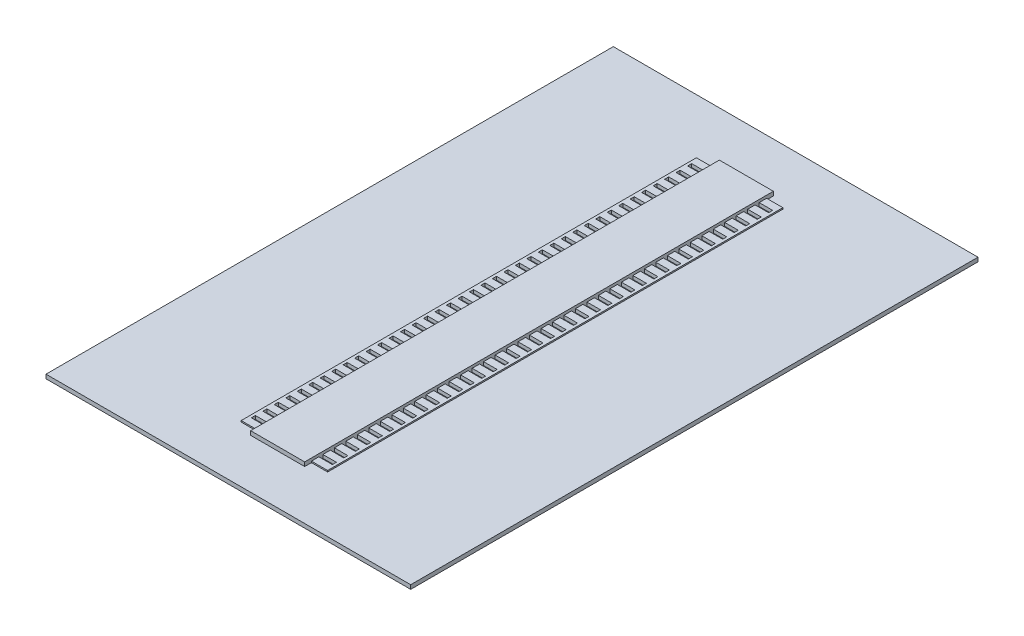
SolidWorks part; units mm, degrees
ref_plane "Front Plane" through (0, 0, 0) normal (0, 0, 1) x (1, 0, 0)
ref_plane "Top Plane" through (0, 0, 0) normal (0, 1, 0) x (1, 0, 0)
ref_plane "Right Plane" through (0, 0, 0) normal (1, 0, 0) x (0, 0, -1)
sketch "Sketch1" plane through (0, 0, 0) normal (0, 1, 0) x (1, 0, 0)
  line L1 (-13.5, 21) -> (13.5, 21)
  line L2 (-13.5, 21) -> (-13.5, -21)
  line L3 (-13.5, -21) -> (13.5, -21)
  line L4 (13.5, 21) -> (13.5, -21)
  line L5 (-13.5, 21) -> (13.5, -21) construction
  line L6 (-13.5, -21) -> (13.5, 21) construction
  point P0 (0, 0)
extrude "Boss-Extrude1" add sketch "Sketch1" along normal blind 0.3
sketch "Sketch2" plane through (0, 0.3, 0) normal (0, 1, 0) x (1, 0, 0)
  line L1 (-2, 17.35) -> (2, 17.35)
  line L2 (-2, 17.35) -> (-2, -17.35)
  line L3 (-2, -17.35) -> (2, -17.35)
  line L4 (2, 17.35) -> (2, -17.35)
  line L5 (-2, 17.35) -> (2, -17.35) construction
  line L6 (-2, -17.35) -> (2, 17.35) construction
  point P0 (0, 0)
extrude "Boss-Extrude2" add sketch "Sketch2" along normal blind 0.3
sketch "Sketch3" plane through (0, 0.3, 0) normal (0, 1, 0) x (1, 0, 0)
  line L0 (2, -17.35) -> (2, 17.35) construction
  line L1 (2, 16.85) -> (3.2, 16.85)
  line L2 (2, 16.85) -> (2, -16.85)
  line L3 (3.2, 16.85) -> (3.2, -16.85)
  line L4 (2, -16.85) -> (3.2, -16.85)
  line L5 (2, -17.35) -> (2, 17.35) construction
  line L6 (-12.7201, 0) -> (12.7201, 0) construction
  line L7 (0, 20.1281) -> (0, -20.1281) construction
  line L8 (-3.2, 16.85) -> (-3.2, -16.85)
  line L9 (-2, -16.85) -> (-3.2, -16.85)
  line L10 (-2, 16.85) -> (-2, -16.85)
  line L11 (-2, 16.85) -> (-3.2, 16.85)
  point P0 (2, 0)
  point P9 (3.2, 0)
  point P13 (0, 0)
  point P17 (0, 0)
extrude "Boss-Extrude4" add sketch "Sketch3" along normal blind 0.1
sketch "Sketch8" plane through (0, 0.4, 0) normal (0, 1, 0) x (1, 0, 0)
  line L0 (2, 16.3) -> (3, 16.3)
  line L1 (2, 16.3) -> (2, 16)
  line L2 (3, 16.3) -> (3, 16)
  line L3 (2, 16) -> (3, 16)
  line L4 (2, 16.85) -> (2, -16.85) construction
  line L5 (-3, 16.3) -> (-2, 16.3)
  line L6 (-3, 16.3) -> (-3, 16)
  line L7 (-3, 16) -> (-2, 16)
  line L8 (-2, 16.3) -> (-2, 16)
  line L9 (-3, 15.45) -> (-2, 15.45)
  line L10 (-3, 15.45) -> (-3, 15.15)
  line L11 (-3, 15.15) -> (-2, 15.15)
  line L12 (-2, 15.45) -> (-2, 15.15)
  line L13 (-3, 14.6) -> (-2, 14.6)
  line L14 (-3, 14.6) -> (-3, 14.3)
  line L15 (-3, 14.3) -> (-2, 14.3)
  line L16 (-2, 14.6) -> (-2, 14.3)
  line L17 (-3, 13.75) -> (-2, 13.75)
  line L18 (-3, 13.75) -> (-3, 13.45)
  line L19 (-3, 13.45) -> (-2, 13.45)
  line L20 (-2, 13.75) -> (-2, 13.45)
  line L21 (-3, 12.9) -> (-2, 12.9)
  line L22 (-3, 12.9) -> (-3, 12.6)
  line L23 (-3, 12.6) -> (-2, 12.6)
  line L24 (-2, 12.9) -> (-2, 12.6)
  line L25 (-3, 12.05) -> (-2, 12.05)
  line L26 (-3, 12.05) -> (-3, 11.75)
  line L27 (-3, 11.75) -> (-2, 11.75)
  line L28 (-2, 12.05) -> (-2, 11.75)
  line L29 (-3, 11.2) -> (-2, 11.2)
  line L30 (-3, 11.2) -> (-3, 10.9)
  line L31 (-3, 10.9) -> (-2, 10.9)
  line L32 (-2, 11.2) -> (-2, 10.9)
  line L33 (-3, 10.35) -> (-2, 10.35)
  line L34 (-3, 10.35) -> (-3, 10.05)
  line L35 (-3, 10.05) -> (-2, 10.05)
  line L36 (-2, 10.35) -> (-2, 10.05)
  line L37 (-3, 9.5) -> (-2, 9.5)
  line L38 (-3, 9.5) -> (-3, 9.2)
  line L39 (-3, 9.2) -> (-2, 9.2)
  line L40 (-2, 9.5) -> (-2, 9.2)
  line L41 (-3, 8.65) -> (-2, 8.65)
  line L42 (-3, 8.65) -> (-3, 8.35)
  line L43 (-3, 8.35) -> (-2, 8.35)
  line L44 (-2, 8.65) -> (-2, 8.35)
  line L45 (-3, 7.8) -> (-2, 7.8)
  line L46 (-3, 7.8) -> (-3, 7.5)
  line L47 (-3, 7.5) -> (-2, 7.5)
  line L48 (-2, 7.8) -> (-2, 7.5)
  line L49 (-3, 6.95) -> (-2, 6.95)
  line L50 (-3, 6.95) -> (-3, 6.65)
  line L51 (-3, 6.65) -> (-2, 6.65)
  line L52 (-2, 6.95) -> (-2, 6.65)
  line L53 (-3, 6.1) -> (-2, 6.1)
  line L54 (-3, 6.1) -> (-3, 5.8)
  line L55 (-3, 5.8) -> (-2, 5.8)
  line L56 (-2, 6.1) -> (-2, 5.8)
  line L57 (-3, 5.25) -> (-2, 5.25)
  line L58 (-3, 5.25) -> (-3, 4.95)
  line L59 (-3, 4.95) -> (-2, 4.95)
  line L60 (-2, 5.25) -> (-2, 4.95)
  line L61 (-3, 4.4) -> (-2, 4.4)
  line L62 (-3, 4.4) -> (-3, 4.1)
  line L63 (-3, 4.1) -> (-2, 4.1)
  line L64 (-2, 4.4) -> (-2, 4.1)
  line L65 (-3, 3.55) -> (-2, 3.55)
  line L66 (-3, 3.55) -> (-3, 3.25)
  line L67 (-3, 3.25) -> (-2, 3.25)
  line L68 (-2, 3.55) -> (-2, 3.25)
  line L69 (-3, 2.7) -> (-2, 2.7)
  line L70 (-3, 2.7) -> (-3, 2.4)
  line L71 (-3, 2.4) -> (-2, 2.4)
  line L72 (-2, 2.7) -> (-2, 2.4)
  line L73 (-3, 1.85) -> (-2, 1.85)
  line L74 (-3, 1.85) -> (-3, 1.55)
  line L75 (-3, 1.55) -> (-2, 1.55)
  line L76 (-2, 1.85) -> (-2, 1.55)
  line L77 (-3, 1) -> (-2, 1)
  line L78 (-3, 1) -> (-3, 0.7)
  line L79 (-3, 0.7) -> (-2, 0.7)
  line L80 (-2, 1) -> (-2, 0.7)
  line L81 (-3, 0.15) -> (-2, 0.15)
  line L82 (-3, 0.15) -> (-3, -0.15)
  line L83 (-3, -0.15) -> (-2, -0.15)
  line L84 (-2, 0.15) -> (-2, -0.15)
  line L85 (-3, -0.7) -> (-2, -0.7)
  line L86 (-3, -0.7) -> (-3, -1)
  line L87 (-3, -1) -> (-2, -1)
  line L88 (-2, -0.7) -> (-2, -1)
  line L89 (-3, -1.55) -> (-2, -1.55)
  line L90 (-3, -1.55) -> (-3, -1.85)
  line L91 (-3, -1.85) -> (-2, -1.85)
  line L92 (-2, -1.55) -> (-2, -1.85)
  line L93 (-3, -2.4) -> (-2, -2.4)
  line L94 (-3, -2.4) -> (-3, -2.7)
  line L95 (-3, -2.7) -> (-2, -2.7)
  line L96 (-2, -2.4) -> (-2, -2.7)
  line L97 (-3, -3.25) -> (-2, -3.25)
  line L98 (-3, -3.25) -> (-3, -3.55)
  line L99 (-3, -3.55) -> (-2, -3.55)
  line L100 (-2, -3.25) -> (-2, -3.55)
  line L101 (-3, -4.1) -> (-2, -4.1)
  line L102 (-3, -4.1) -> (-3, -4.4)
  line L103 (-3, -4.4) -> (-2, -4.4)
  line L104 (-2, -4.1) -> (-2, -4.4)
  line L105 (-3, -4.95) -> (-2, -4.95)
  line L106 (-3, -4.95) -> (-3, -5.25)
  line L107 (-3, -5.25) -> (-2, -5.25)
  line L108 (-2, -4.95) -> (-2, -5.25)
  line L109 (-3, -5.8) -> (-2, -5.8)
  line L110 (-3, -5.8) -> (-3, -6.1)
  line L111 (-3, -6.1) -> (-2, -6.1)
  line L112 (-2, -5.8) -> (-2, -6.1)
  line L113 (-3, -6.65) -> (-2, -6.65)
  line L114 (-3, -6.65) -> (-3, -6.95)
  line L115 (-3, -6.95) -> (-2, -6.95)
  line L116 (-2, -6.65) -> (-2, -6.95)
  line L117 (-3, -7.5) -> (-2, -7.5)
  line L118 (-3, -7.5) -> (-3, -7.8)
  line L119 (-3, -7.8) -> (-2, -7.8)
  line L120 (-2, -7.5) -> (-2, -7.8)
  line L121 (-3, -8.35) -> (-2, -8.35)
  line L122 (-3, -8.35) -> (-3, -8.65)
  line L123 (-3, -8.65) -> (-2, -8.65)
  line L124 (-2, -8.35) -> (-2, -8.65)
  line L125 (-3, -9.2) -> (-2, -9.2)
  line L126 (-3, -9.2) -> (-3, -9.5)
  line L127 (-3, -9.5) -> (-2, -9.5)
  line L128 (-2, -9.2) -> (-2, -9.5)
  line L129 (-3, -10.05) -> (-2, -10.05)
  line L130 (-3, -10.05) -> (-3, -10.35)
  line L131 (-3, -10.35) -> (-2, -10.35)
  line L132 (-2, -10.05) -> (-2, -10.35)
  line L133 (-3, -10.9) -> (-2, -10.9)
  line L134 (-3, -10.9) -> (-3, -11.2)
  line L135 (-3, -11.2) -> (-2, -11.2)
  line L136 (-2, -10.9) -> (-2, -11.2)
  line L137 (-3, -11.75) -> (-2, -11.75)
  line L138 (-3, -11.75) -> (-3, -12.05)
  line L139 (-3, -12.05) -> (-2, -12.05)
  line L140 (-2, -11.75) -> (-2, -12.05)
  line L141 (-3, -12.6) -> (-2, -12.6)
  line L142 (-3, -12.6) -> (-3, -12.9)
  line L143 (-3, -12.9) -> (-2, -12.9)
  line L144 (-2, -12.6) -> (-2, -12.9)
  line L145 (-3, -13.45) -> (-2, -13.45)
  line L146 (-3, -13.45) -> (-3, -13.75)
  line L147 (-3, -13.75) -> (-2, -13.75)
  line L148 (-2, -13.45) -> (-2, -13.75)
  line L149 (-3, -14.3) -> (-2, -14.3)
  line L150 (-3, -14.3) -> (-3, -14.6)
  line L151 (-3, -14.6) -> (-2, -14.6)
  line L152 (-2, -14.3) -> (-2, -14.6)
  line L153 (-3, -15.15) -> (-2, -15.15)
  line L154 (-3, -15.15) -> (-3, -15.45)
  line L155 (-3, -15.45) -> (-2, -15.45)
  line L156 (-2, -15.15) -> (-2, -15.45)
  line L157 (-3, -16) -> (-2, -16)
  line L158 (-3, -16) -> (-3, -16.3)
  line L159 (-3, -16.3) -> (-2, -16.3)
  line L160 (-2, -16) -> (-2, -16.3)
  line L161 (2, 15.45) -> (3, 15.45)
  line L162 (2, 15.45) -> (2, 15.15)
  line L163 (2, 15.15) -> (3, 15.15)
  line L164 (3, 15.45) -> (3, 15.15)
  line L165 (2, 14.6) -> (3, 14.6)
  line L166 (2, 14.6) -> (2, 14.3)
  line L167 (2, 14.3) -> (3, 14.3)
  line L168 (3, 14.6) -> (3, 14.3)
  line L169 (2, 13.75) -> (3, 13.75)
  line L170 (2, 13.75) -> (2, 13.45)
  line L171 (2, 13.45) -> (3, 13.45)
  line L172 (3, 13.75) -> (3, 13.45)
  line L173 (2, 12.9) -> (3, 12.9)
  line L174 (2, 12.9) -> (2, 12.6)
  line L175 (2, 12.6) -> (3, 12.6)
  line L176 (3, 12.9) -> (3, 12.6)
  line L177 (2, 12.05) -> (3, 12.05)
  line L178 (2, 12.05) -> (2, 11.75)
  line L179 (2, 11.75) -> (3, 11.75)
  line L180 (3, 12.05) -> (3, 11.75)
  line L181 (2, 11.2) -> (3, 11.2)
  line L182 (2, 11.2) -> (2, 10.9)
  line L183 (2, 10.9) -> (3, 10.9)
  line L184 (3, 11.2) -> (3, 10.9)
  line L185 (2, 10.35) -> (3, 10.35)
  line L186 (2, 10.35) -> (2, 10.05)
  line L187 (2, 10.05) -> (3, 10.05)
  line L188 (3, 10.35) -> (3, 10.05)
  line L189 (2, 9.5) -> (3, 9.5)
  line L190 (2, 9.5) -> (2, 9.2)
  line L191 (2, 9.2) -> (3, 9.2)
  line L192 (3, 9.5) -> (3, 9.2)
  line L193 (2, 8.65) -> (3, 8.65)
  line L194 (2, 8.65) -> (2, 8.35)
  line L195 (2, 8.35) -> (3, 8.35)
  line L196 (3, 8.65) -> (3, 8.35)
  line L197 (2, 7.8) -> (3, 7.8)
  line L198 (2, 7.8) -> (2, 7.5)
  line L199 (2, 7.5) -> (3, 7.5)
  line L200 (3, 7.8) -> (3, 7.5)
  line L201 (2, 6.95) -> (3, 6.95)
  line L202 (2, 6.95) -> (2, 6.65)
  line L203 (2, 6.65) -> (3, 6.65)
  line L204 (3, 6.95) -> (3, 6.65)
  line L205 (2, 6.1) -> (3, 6.1)
  line L206 (2, 6.1) -> (2, 5.8)
  line L207 (2, 5.8) -> (3, 5.8)
  line L208 (3, 6.1) -> (3, 5.8)
  line L209 (2, 5.25) -> (3, 5.25)
  line L210 (2, 5.25) -> (2, 4.95)
  line L211 (2, 4.95) -> (3, 4.95)
  line L212 (3, 5.25) -> (3, 4.95)
  line L213 (2, 4.4) -> (3, 4.4)
  line L214 (2, 4.4) -> (2, 4.1)
  line L215 (2, 4.1) -> (3, 4.1)
  line L216 (3, 4.4) -> (3, 4.1)
  line L217 (2, 3.55) -> (3, 3.55)
  line L218 (2, 3.55) -> (2, 3.25)
  line L219 (2, 3.25) -> (3, 3.25)
  line L220 (3, 3.55) -> (3, 3.25)
  line L221 (2, 2.7) -> (3, 2.7)
  line L222 (2, 2.7) -> (2, 2.4)
  line L223 (2, 2.4) -> (3, 2.4)
  line L224 (3, 2.7) -> (3, 2.4)
  line L225 (2, 1.85) -> (3, 1.85)
  line L226 (2, 1.85) -> (2, 1.55)
  line L227 (2, 1.55) -> (3, 1.55)
  line L228 (3, 1.85) -> (3, 1.55)
  line L229 (2, 1) -> (3, 1)
  line L230 (2, 1) -> (2, 0.7)
  line L231 (2, 0.7) -> (3, 0.7)
  line L232 (3, 1) -> (3, 0.7)
  line L233 (2, 0.15) -> (3, 0.15)
  line L234 (2, 0.15) -> (2, -0.15)
  line L235 (2, -0.15) -> (3, -0.15)
  line L236 (3, 0.15) -> (3, -0.15)
  line L237 (2, -0.7) -> (3, -0.7)
  line L238 (2, -0.7) -> (2, -1)
  line L239 (2, -1) -> (3, -1)
  line L240 (3, -0.7) -> (3, -1)
  line L241 (2, -1.55) -> (3, -1.55)
  line L242 (2, -1.55) -> (2, -1.85)
  line L243 (2, -1.85) -> (3, -1.85)
  line L244 (3, -1.55) -> (3, -1.85)
  line L245 (2, -2.4) -> (3, -2.4)
  line L246 (2, -2.4) -> (2, -2.7)
  line L247 (2, -2.7) -> (3, -2.7)
  line L248 (3, -2.4) -> (3, -2.7)
  line L249 (2, -3.25) -> (3, -3.25)
  line L250 (2, -3.25) -> (2, -3.55)
  line L251 (2, -3.55) -> (3, -3.55)
  line L252 (3, -3.25) -> (3, -3.55)
  line L253 (2, -4.1) -> (3, -4.1)
  line L254 (2, -4.1) -> (2, -4.4)
  line L255 (2, -4.4) -> (3, -4.4)
  line L256 (3, -4.1) -> (3, -4.4)
  line L257 (2, -4.95) -> (3, -4.95)
  line L258 (2, -4.95) -> (2, -5.25)
  line L259 (2, -5.25) -> (3, -5.25)
  line L260 (3, -4.95) -> (3, -5.25)
  line L261 (2, -5.8) -> (3, -5.8)
  line L262 (2, -5.8) -> (2, -6.1)
  line L263 (2, -6.1) -> (3, -6.1)
  line L264 (3, -5.8) -> (3, -6.1)
  line L265 (2, -6.65) -> (3, -6.65)
  line L266 (2, -6.65) -> (2, -6.95)
  line L267 (2, -6.95) -> (3, -6.95)
  line L268 (3, -6.65) -> (3, -6.95)
  line L269 (2, -7.5) -> (3, -7.5)
  line L270 (2, -7.5) -> (2, -7.8)
  line L271 (2, -7.8) -> (3, -7.8)
  line L272 (3, -7.5) -> (3, -7.8)
  line L273 (2, -8.35) -> (3, -8.35)
  line L274 (2, -8.35) -> (2, -8.65)
  line L275 (2, -8.65) -> (3, -8.65)
  line L276 (3, -8.35) -> (3, -8.65)
  line L277 (2, -9.2) -> (3, -9.2)
  line L278 (2, -9.2) -> (2, -9.5)
  line L279 (2, -9.5) -> (3, -9.5)
  line L280 (3, -9.2) -> (3, -9.5)
  line L281 (2, -10.05) -> (3, -10.05)
  line L282 (2, -10.05) -> (2, -10.35)
  line L283 (2, -10.35) -> (3, -10.35)
  line L284 (3, -10.05) -> (3, -10.35)
  line L285 (2, -10.9) -> (3, -10.9)
  line L286 (2, -10.9) -> (2, -11.2)
  line L287 (2, -11.2) -> (3, -11.2)
  line L288 (3, -10.9) -> (3, -11.2)
  line L289 (2, -11.75) -> (3, -11.75)
  line L290 (2, -11.75) -> (2, -12.05)
  line L291 (2, -12.05) -> (3, -12.05)
  line L292 (3, -11.75) -> (3, -12.05)
  line L293 (2, -12.6) -> (3, -12.6)
  line L294 (2, -12.6) -> (2, -12.9)
  line L295 (2, -12.9) -> (3, -12.9)
  line L296 (3, -12.6) -> (3, -12.9)
  line L297 (2, -13.45) -> (3, -13.45)
  line L298 (2, -13.45) -> (2, -13.75)
  line L299 (2, -13.75) -> (3, -13.75)
  line L300 (3, -13.45) -> (3, -13.75)
  line L301 (2, -14.3) -> (3, -14.3)
  line L302 (2, -14.3) -> (2, -14.6)
  line L303 (2, -14.6) -> (3, -14.6)
  line L304 (3, -14.3) -> (3, -14.6)
  line L305 (2, -15.15) -> (3, -15.15)
  line L306 (2, -15.15) -> (2, -15.45)
  line L307 (2, -15.45) -> (3, -15.45)
  line L308 (3, -15.15) -> (3, -15.45)
  line L309 (2, -16) -> (3, -16)
  line L310 (2, -16) -> (2, -16.3)
  line L311 (2, -16.3) -> (3, -16.3)
  line L312 (3, -16) -> (3, -16.3)
  dimension "D1" = 0.55
  dimension "D2" = 2
  dimension "D3" = 39
extrude "Cut-Extrude2" cut sketch "Sketch8" against normal blind 0.25
sketch "Sketch11" plane through (0, 0.3, 0) normal (0, 1, 0) x (1, 0, 0)
  line L0 (-12.152, 0) -> (12.152, 0) construction
  line L1 (0, 19.572) -> (0, -19.572) construction
  line L2 (2, 17.35) -> (-2, 17.35) construction
  line L3 (-6.6, 19.85) -> (6.6, 19.85)
  line L4 (-5.6, 18.85) -> (5.6, 18.85)
  line L5 (-6.6, 19.85) -> (-6.6, -0.5)
  line L6 (-6, -0.5) -> (-6.6, -0.5)
  line L9 (-3.2, 16.85) -> (-3.2, -16.85) construction
  line L10 (-3.2, 16.85) -> (-3.2, -16.85) construction
  line L11 (-3.4, 15.5469) -> (-3.2, 15.5469)
  line L12 (-3.2, 13.9406) -> (-3.4, 13.9406)
  line L13 (-3.4, 13.9406) -> (-3.4, 15.5469)
  line L14 (-3.9, 16.0469) -> (-3.2, 16.0469)
  line L15 (-3.2, 13.4406) -> (-3.9, 13.4406)
  line L16 (-3.2, 14.7438) -> (-3.9427, 14.7438) construction
  line L17 (-3.9, 16.0469) -> (-3.9, 14.9938)
  line L18 (-3.9, 13.4406) -> (-3.9, 14.4938)
  line L19 (-3.9, 11.8344) -> (-3.2, 11.8344)
  line L20 (-3.9, 11.8344) -> (-3.9, 10.7813)
  line L21 (-3.4, 9.7281) -> (-3.4, 11.3344)
  line L22 (-3.4, 11.3344) -> (-3.2, 11.3344)
  line L23 (-3.2, 9.7281) -> (-3.4, 9.7281)
  line L24 (-3.2, 9.2281) -> (-3.9, 9.2281)
  line L25 (-3.9, 9.2281) -> (-3.9, 10.2813)
  line L26 (-3.9, 7.6219) -> (-3.2, 7.6219)
  line L27 (-3.9, 7.6219) -> (-3.9, 6.5688)
  line L28 (-3.4, 5.5156) -> (-3.4, 7.1219)
  line L29 (-3.4, 7.1219) -> (-3.2, 7.1219)
  line L30 (-3.2, 5.5156) -> (-3.4, 5.5156)
  line L31 (-3.2, 5.0156) -> (-3.9, 5.0156)
  line L32 (-3.9, 5.0156) -> (-3.9, 6.0688)
  line L33 (-3.9, 3.4094) -> (-3.2, 3.4094)
  line L34 (-3.9, 3.4094) -> (-3.9, 2.3563)
  line L35 (-3.4, 1.3031) -> (-3.4, 2.9094)
  line L36 (-3.4, 2.9094) -> (-3.2, 2.9094)
  line L37 (-3.2, 1.3031) -> (-3.4, 1.3031)
  line L38 (-3.2, 0.8031) -> (-3.9, 0.8031)
  line L39 (-3.9, 0.8031) -> (-3.9, 1.8563)
  line L40 (-3.9, -0.8031) -> (-3.2, -0.8031)
  line L41 (-3.9, -0.8031) -> (-3.9, -1.8562)
  line L42 (-3.4, -2.9094) -> (-3.4, -1.3031)
  line L43 (-3.4, -1.3031) -> (-3.2, -1.3031)
  line L44 (-3.2, -2.9094) -> (-3.4, -2.9094)
  line L45 (-3.2, -3.4094) -> (-3.9, -3.4094)
  line L46 (-3.9, -3.4094) -> (-3.9, -2.3562)
  line L47 (-3.9, -5.0156) -> (-3.2, -5.0156)
  line L48 (-3.9, -5.0156) -> (-3.9, -6.0687)
  line L49 (-3.4, -7.1219) -> (-3.4, -5.5156)
  line L50 (-3.4, -5.5156) -> (-3.2, -5.5156)
  line L51 (-3.2, -7.1219) -> (-3.4, -7.1219)
  line L52 (-3.2, -7.6219) -> (-3.9, -7.6219)
  line L53 (-3.9, -7.6219) -> (-3.9, -6.5687)
  line L54 (-3.9, -9.2281) -> (-3.2, -9.2281)
  line L55 (-3.9, -9.2281) -> (-3.9, -10.2812)
  line L56 (-3.4, -11.3344) -> (-3.4, -9.7281)
  line L57 (-3.4, -9.7281) -> (-3.2, -9.7281)
  line L58 (-3.2, -11.3344) -> (-3.4, -11.3344)
  line L59 (-3.2, -11.8344) -> (-3.9, -11.8344)
  line L60 (-3.9, -11.8344) -> (-3.9, -10.7812)
  line L61 (-3.9, -13.4406) -> (-3.2, -13.4406)
  line L62 (-3.9, -13.4406) -> (-3.9, -14.4937)
  line L63 (-3.4, -15.5469) -> (-3.4, -13.9406)
  line L64 (-3.4, -13.9406) -> (-3.2, -13.9406)
  line L65 (-3.2, -15.5469) -> (-3.4, -15.5469)
  line L66 (-3.2, -16.0469) -> (-3.9, -16.0469)
  line L67 (-3.9, -16.0469) -> (-3.9, -14.9937)
  line L68 (-3.9, 10.7813) -> (-4.1, 10.7813)
  line L69 (-3.9, 14.4938) -> (-4.1, 14.4938)
  line L70 (-4.1, 14.4938) -> (-4.1, 10.7813)
  line L71 (-3.9, 14.9938) -> (-4.6, 14.9938)
  line L72 (-3.9, 10.2813) -> (-4.6, 10.2813)
  line L73 (-3.2, 12.6375) -> (-4.7955, 12.6375) construction
  line L74 (-4.6, 12.3875) -> (-4.6, 10.2813)
  line L75 (-4.6, 14.9938) -> (-4.6, 12.8875)
  line L76 (-3.9, 6.5688) -> (-4.6, 6.5688)
  line L77 (-4.6, 6.5688) -> (-4.6, 4.4625)
  line L78 (-3.9, 1.8563) -> (-4.6, 1.8563)
  line L79 (-4.6, 1.8563) -> (-4.6, 3.9625)
  line L80 (-3.9, 6.0688) -> (-4.1, 6.0688)
  line L81 (-4.1, 6.0688) -> (-4.1, 2.3563)
  line L82 (-4.1, 2.3563) -> (-3.9, 2.3563)
  line L83 (-3.2, 4.2125) -> (-5.0289, 4.2125) construction
  line L84 (-3.9, -1.8562) -> (-4.6, -1.8562)
  line L85 (-4.6, -1.8562) -> (-4.6, -3.9625)
  line L86 (-3.9, -6.5687) -> (-4.6, -6.5687)
  line L87 (-4.6, -4.4625) -> (-4.6, -6.5687)
  line L88 (-3.9, -2.3562) -> (-4.1, -2.3562)
  line L89 (-4.1, -2.3562) -> (-4.1, -6.0687)
  line L90 (-4.1, -6.0687) -> (-3.9, -6.0687)
  line L91 (-3.2, -4.2125) -> (-4.7465, -4.2125) construction
  line L92 (-3.9, -10.2812) -> (-4.6, -10.2812)
  line L93 (-4.6, -10.2812) -> (-4.6, -12.3875)
  line L94 (-3.9, -14.9937) -> (-4.6, -14.9937)
  line L95 (-4.6, -14.9937) -> (-4.6, -12.8875)
  line L96 (-3.9, -10.7812) -> (-4.1, -10.7812)
  line L97 (-3.9, -14.4937) -> (-4.1, -14.4937)
  line L98 (-4.1, -14.4937) -> (-4.1, -10.7812)
  line L99 (-3.2, -12.6375) -> (-4.7169, -12.6375) construction
  line L100 (-4.6, 12.8875) -> (-5.3, 12.8875)
  line L101 (-5.3, 12.8875) -> (-5.3, 8.675)
  line L102 (-5.3, 3.9625) -> (-5.3, 8.175)
  line L103 (-5.3, 3.9625) -> (-4.6, 3.9625)
  line L104 (-4.6, 4.4625) -> (-4.8, 4.4625)
  line L105 (-4.8, 4.4625) -> (-4.8, 12.3875)
  line L106 (-4.8, 12.3875) -> (-4.6, 12.3875)
  line L107 (-3.2, 8.425) -> (-5.4058, 8.425) construction
  line L108 (-4.6, -3.9625) -> (-5.3, -3.9625)
  line L109 (-5.3, -3.9625) -> (-5.3, -8.2423)
  line L110 (-4.6, -12.8875) -> (-5.3, -12.8875)
  line L111 (-5.3, -8.7423) -> (-5.3, -12.8875)
  line L112 (-4.8, -12.3875) -> (-4.6, -12.3875)
  line L113 (-4.8, -12.3875) -> (-4.8, -4.4625)
  line L114 (-4.8, -4.4625) -> (-4.6, -4.4625)
  line L115 (-5.5126, -8.4923) -> (-3.2, -8.4923) construction
  line L116 (-5.3, 8.675) -> (-6, 8.675)
  line L117 (-6, 8.675) -> (-6, 0.5)
  line L120 (-6, -8.7423) -> (-6, -0.5)
  line L121 (-6, -8.7423) -> (-5.3, -8.7423)
  line L122 (-5.3, -8.2423) -> (-5.5, -8.2423)
  line L123 (-5.5, -8.2423) -> (-5.5, 8.175)
  line L124 (-5.5, 8.175) -> (-5.3, 8.175)
  circle A0 centre (0, 19.35) radius 0.9
  point P0 (0, 19.35)
  point P3 (-3.2, 15.5469)
  point P4 (0, 0)
  point P8 (0, 0)
  point P9 (0, 17.35)
  point P14 (0, 19.85)
  point P15 (0, 18.85)
  point P16 (-3.2, 16.85)
  point P19 (0, 19.85)
  point P22 (0, 18.85)
  point P27 (-3.2, 15.7969)
  point P29 (-3.2, 14.7438)
  point P30 (-3.2, 13.6906)
  point P31 (-3.2, 12.6375)
  point P32 (-3.2, 11.5844)
  point P33 (-3.2, 10.5312)
  point P34 (-3.2, 9.4781)
  point P35 (-3.2, 8.425)
  point P36 (-3.2, 7.3719)
  point P37 (-3.2, 6.3187)
  point P38 (-3.2, 5.2656)
  point P39 (-3.2, 4.2125)
  point P40 (-3.2, 3.1594)
  point P41 (-3.2, 2.1063)
  point P42 (-3.2, 1.0531)
  point P43 (-3.2, 0)
  point P44 (-3.2, -1.0531)
  point P45 (-3.2, -2.1063)
  point P46 (-3.2, -3.1594)
  point P47 (-3.2, -4.2125)
  point P48 (-3.2, -5.2656)
  point P49 (-3.2, -6.3188)
  point P50 (-3.2, -7.3719)
  point P51 (-3.2, -8.425)
  point P52 (-3.2, -9.4781)
  point P53 (-3.2, -10.5312)
  point P54 (-3.2, -11.5844)
  point P55 (-3.2, -12.6375)
  point P56 (-3.2, -13.6906)
  point P57 (-3.2, -14.7438)
  point P58 (-3.2, -15.7969)
  point P59 (-3.2, -16.85)
  point P62 (-3.2, 13.9406)
  point P63 (-3.2, 16.0469)
  point P66 (-3.2, 13.4406)
  point P77 (-3.9, 14.7438)
  point P158 (-4.6, 12.6375)
  point P167 (-4.6, 4.2125)
  point P176 (-4.6, -4.2125)
  point P185 (-4.6, -12.6375)
  point P194 (-5.3, 8.425)
  point P203 (-5.3, -8.4923)
  dimension "D1" = 0.5
  dimension "2" = 2
  dimension "D2" = 0.5
  dimension "D3" = 33
  dimension "D4" = 0.25
  dimension "D5" = 0.25
  dimension "D6" = 0.25
  dimension "D7" = 0.25
  dimension "D8" = 0.25
  dimension "D9" = 0.25
  dimension "D11" = 0.25
  dimension "D12" = 0.25
  dimension "D13" = 0.25
  dimension "D14" = 0.25
  dimension "D15" = 0.25
  dimension "D16" = 0.25
  dimension "D17" = 0.25
  dimension "D18" = 0.25
  dimension "D19" = 0.25
  dimension "D20" = 0.25
  dimension "D21" = 0.25
  dimension "D22" = 0.25
  dimension "D10" = 8
